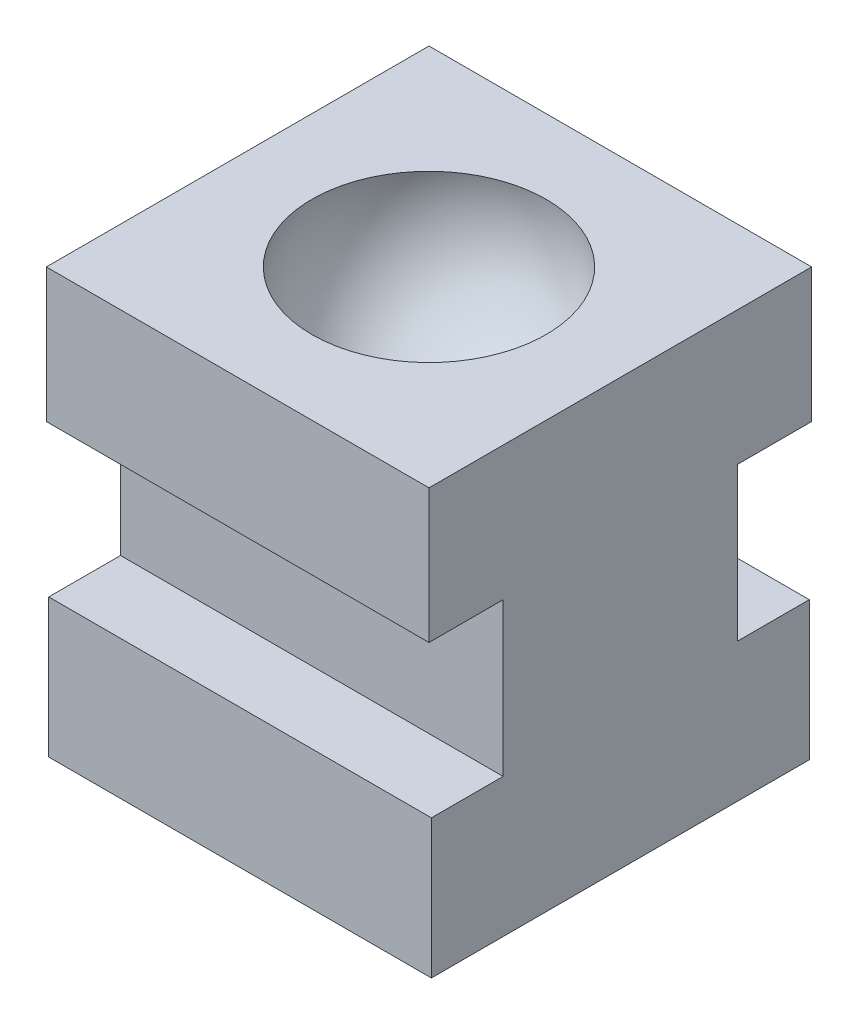
SolidWorks part; units mm, degrees
material "ABS"
ref_plane "Front Plane" through (0, 0, 0) normal (0, 0, 1) x (1, 0, 0)
ref_plane "Top Plane" through (0, 0, 0) normal (0, 1, 0) x (1, 0, 0)
ref_plane "Right Plane" through (0, 0, 0) normal (1, 0, 0) x (0, 0, -1)
sketch "Sketch1" plane through (0, 0, 0) normal (0, 1, 0) x (1, 0, 0)
  line L1 (0, 0) -> (8, 0)
  line L2 (0, 0) -> (0, 7.9)
  line L3 (0, 7.9) -> (8, 7.9)
  line L4 (8, 0) -> (8, 7.9)
  dimension "D1" = 8
  dimension "D2" = 7.9
extrude "Boss-Extrude1" add sketch "Sketch1" along normal blind 2.9
sketch "Sketch2" plane through (0, 2.9, 0) normal (0, 1, 0) x (1, 0, 0)
  line L0 (0, 7.9) -> (8, 0) construction
  line L1 (8, 7.9) -> (0, 0) construction
  line L2 (0, 7.9) -> (0, 0) construction
  line L3 (8, 6.4) -> (0, 6.4)
  line L4 (8, 6.4) -> (8, 1.5)
  line L5 (8, 1.5) -> (0, 1.5)
  line L6 (0, 6.4) -> (0, 1.5)
  point P8 (4, 3.95)
  dimension "D1" = 4.9
extrude "Boss-Extrude2" add sketch "Sketch2" along normal blind 6
ref_plane "Plane1" through (4, 0, 0) normal (-1, 0, 0) x (0, 0, 1)
sketch "Sketch3" plane through (4, 0, 0) normal (-1, 0, 0) x (0, 0, 1)
  line L0 (-6.4, 8.9) -> (-1.5, 8.9) construction
  line L1 (-3.95, 8.9) -> (-3.95, -0.941) construction
  line L2 (-3.95, 8.9) -> (-3.95, 5.9)
  line L3 (-3.95, 8.9) -> (-6.3995, 8.9)
  circle A0 centre (-3.95, 8.4) radius 2.5 construction
  arc A1 (-6.3995, 8.9) -> (-3.95, 5.9) centre (-3.95, 8.4) ccw
  dimension "D1" = 5
  dimension "D2" = 0.5
sketch "Sketch4" plane through (0, 0, 0) normal (-1, 0, 0) x (0, 0, 1)
  line L0 (-3.95, 8.9) -> (-3.95, 5.9) construction
  line L1 (0.05, 6.1) -> (-7.95, 6.1)
  line L2 (0.05, 6.1) -> (0.05, 8.9)
  line L3 (0.05, 8.9) -> (-7.95, 8.9)
  line L4 (-7.95, 6.1) -> (-7.95, 8.9)
  line L5 (0.05, 6.1) -> (-7.95, 8.9) construction
  line L6 (0.05, 8.9) -> (-7.95, 6.1) construction
  line L7 (-1.5, 2.9) -> (0, 2.9) construction
  line L8 (-6.4, 8.9) -> (-1.5, 8.9) construction
  point P0 (-3.95, 7.5)
  point P9 (-0.75, 2.9)
  dimension "D1" = 8
  dimension "D2" = 3.2
  dimension "D3" = 0
extrude "Boss-Extrude3" add sketch "Sketch4" against normal through all
revolve "Cut-Revolve2" cut sketch "Sketch3" angle 360 about L2
